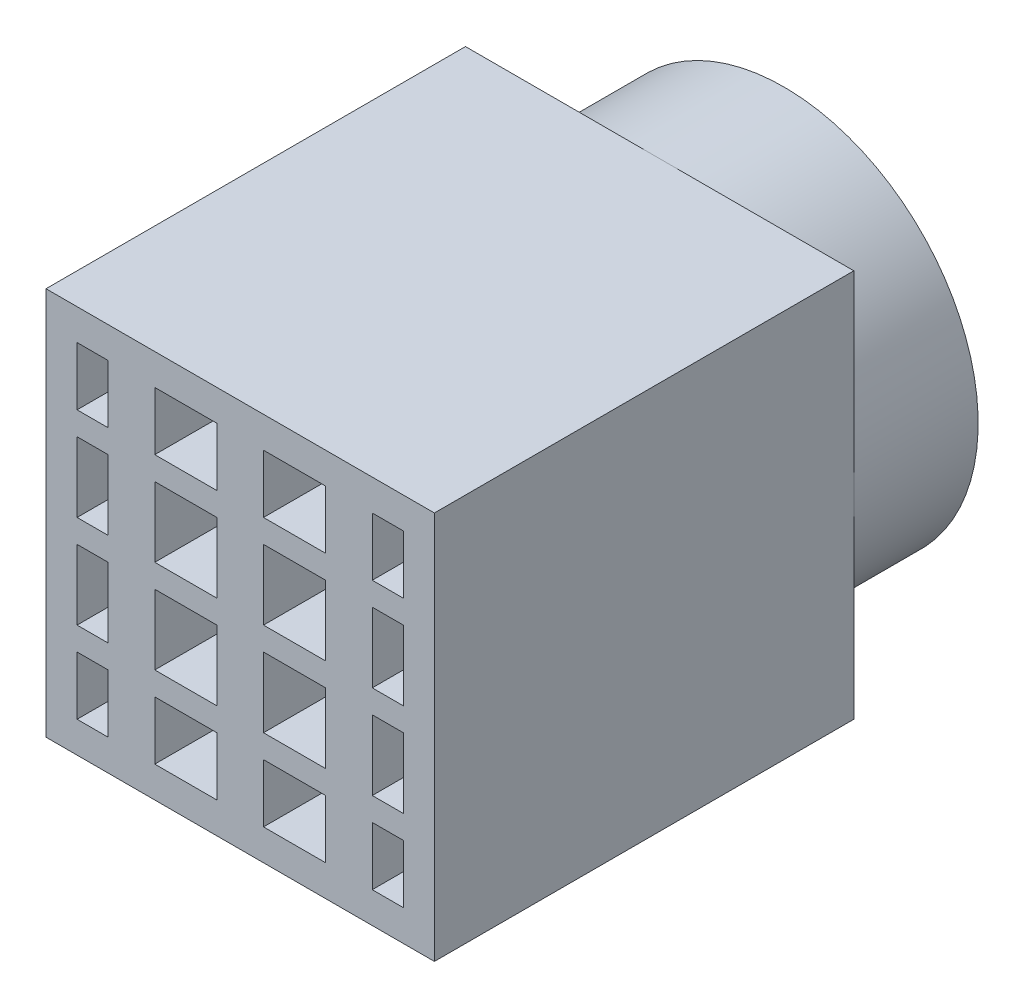
SolidWorks part; units mm, degrees
ref_plane "前视基准面" through (0, 0, 0) normal (0, 0, 1) x (1, 0, 0)
ref_plane "上视基准面" through (0, 0, 0) normal (0, 1, 0) x (1, 0, 0)
ref_plane "右视基准面" through (0, 0, 0) normal (1, 0, 0) x (0, 0, -1)
sketch "草图8" plane through (0, 0, 0) normal (0, 0, 1) x (1, 0, 0)
  line L0 (0, 7.8741) -> (0, -9.2542) construction
  line L1 (-12.5, -12.5) -> (12.5, -12.5)
  line L2 (-12.5, -12.5) -> (-12.5, 12.5)
  line L3 (-12.5, 12.5) -> (12.5, 12.5)
  line L4 (12.5, -12.5) -> (12.5, 12.5)
  line L5 (-12.5, -12.5) -> (12.5, 12.5) construction
  line L6 (-12.5, 12.5) -> (12.5, -12.5) construction
  line L7 (-16.0619, 0) -> (15.5648, 0) construction
  line L8 (-3.5, 7.8741) -> (-3.5, -9.2542) construction
  line L9 (-9.5, 7.8741) -> (-9.5, -9.2542) construction
  line L10 (5.5, 10.5) -> (1.5, 10.5)
  line L15 (-5.5, -10.5) -> (-1.5, -10.5)
  line L20 (-5.5, -10.5) -> (-5.5, 10.5)
  line L21 (-5.5, 10.5) -> (-1.5, 10.5)
  line L26 (-1.5, -10.5) -> (-1.5, 10.5)
  line L27 (-5.5, -10.5) -> (-1.5, 10.5) construction
  line L28 (-5.5, 10.5) -> (-1.5, -10.5) construction
  line L29 (-10.5, -10.5) -> (-8.5, -10.5)
  line L30 (-10.5, -10.5) -> (-10.5, 10.5)
  line L31 (-10.5, 10.5) -> (-8.5, 10.5)
  line L32 (-8.5, -10.5) -> (-8.5, 10.5)
  line L33 (-10.5, -10.5) -> (-8.5, 10.5) construction
  line L34 (-10.5, 10.5) -> (-8.5, -10.5) construction
  line L35 (1.5, -10.5) -> (1.5, 10.5)
  line L36 (5.5, -10.5) -> (1.5, -10.5)
  line L37 (5.5, -10.5) -> (5.5, 10.5)
  line L38 (10.5, 10.5) -> (8.5, 10.5)
  line L39 (8.5, -10.5) -> (8.5, 10.5)
  line L40 (10.5, -10.5) -> (8.5, -10.5)
  line L41 (10.5, -10.5) -> (10.5, 10.5)
  point P0 (0, 0)
  point P14 (-7, 0)
  point P15 (-3.5, 0)
  point P17 (-3, 0)
  point P21 (-9.5, 0)
  point P22 (-9, 0)
  dimension "D1" = 3.5
  dimension "D2" = 6
extrude "凸台-拉伸7" add sketch "草图8" along normal blind 25
sketch "草图9" plane through (0, 0, 0) normal (0, 0, -1) x (-1, 0, 0)
  line L1 (-12.5, -12.5) -> (12.5, -12.5)
  line L2 (-12.5, -12.5) -> (-12.5, 12.5)
  line L3 (-12.5, 12.5) -> (12.5, 12.5)
  line L4 (12.5, -12.5) -> (12.5, 12.5)
  line L5 (-12.5, -12.5) -> (12.5, 12.5) construction
  line L6 (-12.5, 12.5) -> (12.5, -12.5) construction
  point P0 (0, 0)
extrude "凸台-拉伸8" add sketch "草图9" along normal blind 2
sketch "草图14" plane through (0, 0, 25) normal (0, 0, 1) x (1, 0, 0)
  line L0 (-16.6961, 0) -> (20.7273, 0) construction
  line L1 (-12.5, 12.5) -> (-12.5, -12.5) construction
  line L2 (12.5, -0.75) -> (-12.5, -0.75)
  line L3 (12.5, -0.75) -> (12.5, 0.75)
  line L4 (12.5, 0.75) -> (-12.5, 0.75)
  line L5 (-12.5, -0.75) -> (-12.5, 0.75)
  line L6 (12.5, -0.75) -> (-12.5, 0.75) construction
  line L7 (12.5, 0.75) -> (-12.5, -0.75) construction
  line L12 (12.5, 5.25) -> (-12.5, 5.25)
  line L13 (12.5, 5.25) -> (12.5, 6.75)
  line L14 (12.5, 6.75) -> (-12.5, 6.75)
  line L15 (-12.5, 5.25) -> (-12.5, 6.75)
  line L16 (12.5, 5.25) -> (-12.5, 6.75) construction
  line L17 (12.5, 6.75) -> (-12.5, 5.25) construction
  line L18 (12.5, -6.75) -> (-12.5, -5.25) construction
  line L19 (12.5, -5.25) -> (-12.5, -6.75) construction
  line L20 (-12.5, -5.25) -> (-12.5, -6.75)
  line L21 (12.5, -6.75) -> (-12.5, -6.75)
  line L22 (12.5, -5.25) -> (12.5, -6.75)
  line L23 (12.5, -5.25) -> (-12.5, -5.25)
  point P3 (0, 0)
  point P11 (0, 6)
  point P19 (0, -6)
  dimension "D1" = 2
extrude "凸台-拉伸11" add sketch "草图14" against normal blind 25
sketch "草图16" plane through (0, 0, -2) normal (0, 0, -1) x (-1, 0, 0)
  circle A0 centre (0, 0) radius 12.5
  circle A1 centre (0, 0) radius 10
extrude "凸台-拉伸14" add sketch "草图16" along normal blind 6
sketch "草图17" plane through (0, 0, -8) normal (0, 0, -1) x (-1, 0, 0)
  circle A0 centre (0, 0) radius 12.5
extrude "凸台-拉伸15" add sketch "草图17" along normal blind 2
sketch "草图18" plane through (12.5, 0, 0) normal (1, 0, 0) x (0, 0, -1)
  line L0 (-20, 12.5) -> (-20, -12.5)
  line L1 (-25, 12.5) -> (2, 12.5) construction
  line L2 (-25, -12.5) -> (2, -12.5) construction
  line L3 (-25, -12.5) -> (-25, 12.5) construction
  line L4 (-25, -5.9923) -> (2, -5.9923)
  line L5 (2, 0) -> (2, -12.5) construction
  dimension "D1" = 5
sketch "草图19" plane through (-12.5, 0, 0) normal (-1, 0, 0) x (0, 0, 1)
  line L0 (-2, -5.9923) -> (25, -5.9923)
  line L1 (20, 12.5) -> (20, -12.5)
  line L2 (25, -12.5) -> (25, 12.5) construction
